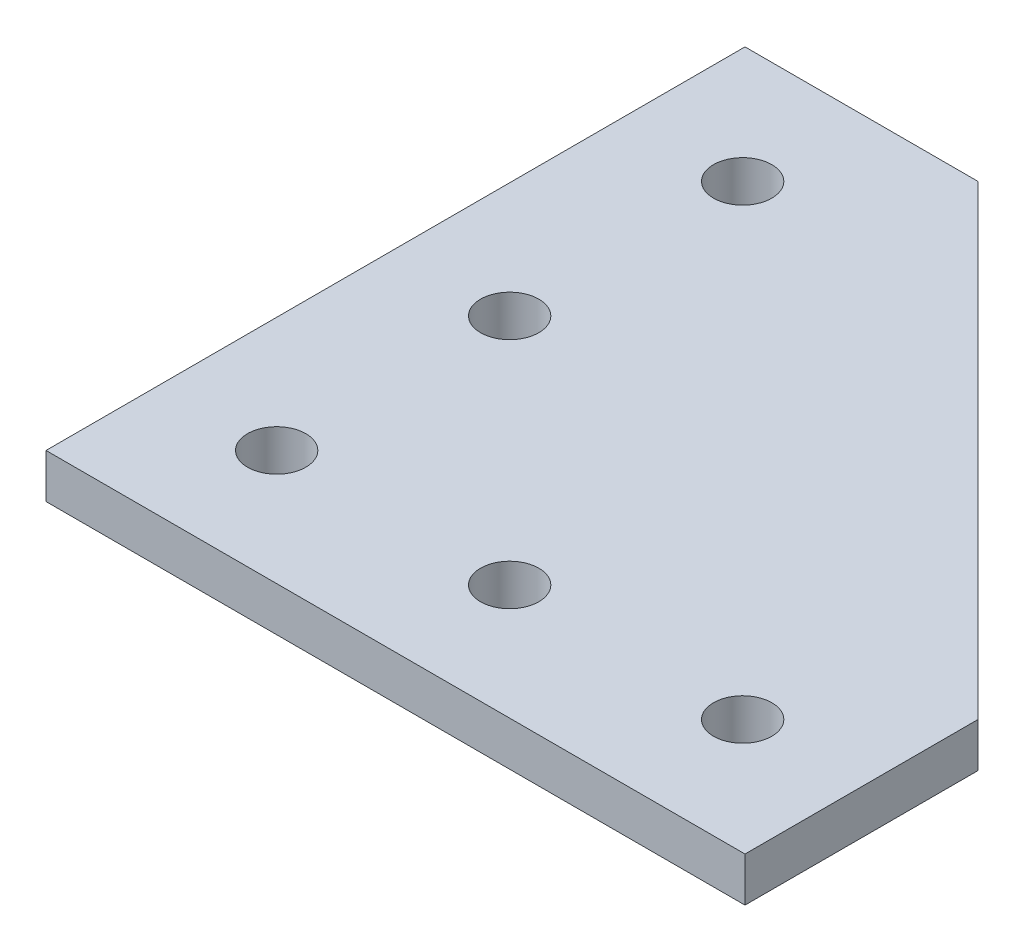
SolidWorks part; units mm, degrees
ref_plane "Front Plane" through (0, 0, 0) normal (0, 0, 1) x (1, 0, 0)
ref_plane "Top Plane" through (0, 0, 0) normal (0, 1, 0) x (1, 0, 0)
ref_plane "Right Plane" through (0, 0, 0) normal (1, 0, 0) x (0, 0, -1)
sketch "Sketch1" plane through (0, 0, 0) normal (0, 1, 0) x (1, 0, 0)
  line L0 (0, 0) -> (76.2, 0)
  line L1 (76.2, 0) -> (76.2, 25.4)
  line L2 (76.2, 25.4) -> (25.4, 76.2)
  line L3 (25.4, 76.2) -> (0, 76.2)
  line L4 (0, 76.2) -> (0, 0)
  line L5 (0, 0) -> (50.8, 50.8) construction
  line L6 (12.573, 9.398) -> (0, 9.398) construction
  circle A0 centre (12.573, 12.573) radius 3.175
  circle A1 centre (37.973, 12.573) radius 3.175
  circle A2 centre (63.373, 12.573) radius 3.175
  circle A3 centre (12.573, 37.973) radius 3.175
  circle A4 centre (12.573, 63.373) radius 3.175
  point P19 (0, 0)
  point P20 (0, 0)
  dimension "D3" = 6.35
  dimension "D5" = 25.4
  dimension "D6" = 25.4
  dimension "D1" = 76.2
  dimension "D2" = 25.4
  dimension "D4" = 9.398
extrude "Boss-Extrude1" add sketch "Sketch1" along normal blind 4.826
